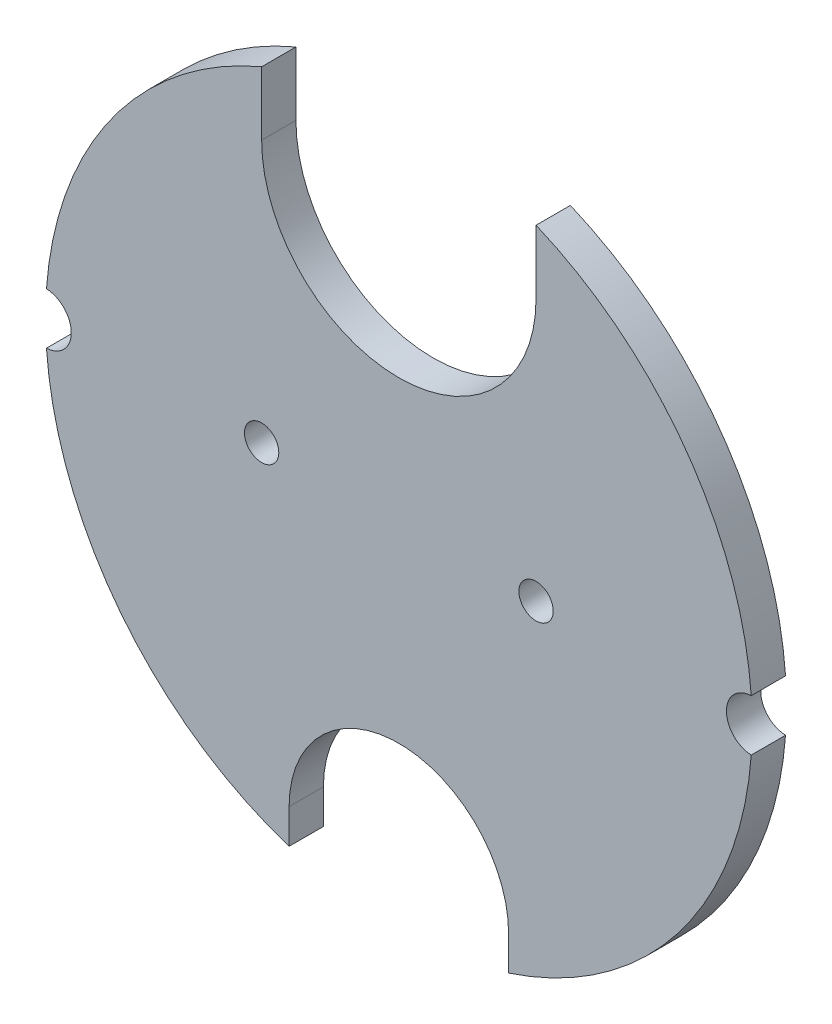
SolidWorks part; units mm, degrees
material "PC High Viscosity"
ref_plane "Front Plane" through (0, 0, 0) normal (0, 0, 1) x (1, 0, 0)
ref_plane "Top Plane" through (0, 0, 0) normal (0, 1, 0) x (1, 0, 0)
ref_plane "Right Plane" through (0, 0, 0) normal (1, 0, 0) x (0, 0, -1)
sketch "Sketch1" plane through (0, 0, 0) normal (0, 0, 1) x (1, 0, 0)
  circle A0 centre (0, 0) radius 65.405
  dimension "D1" = 130.81
extrude "Extrude1" add sketch "Sketch1" along normal blind 6.35
sketch "Sketch2" plane through (0, 0, 6.35) normal (0, 0, 1) x (1, 0, 0)
  line L0 (0, 65.405) -> (0, 48.5098) construction
  line L1 (-25.4, 48.5098) -> (-25.4, 60.2715)
  line L2 (-25.4, 60.2715) -> (-25.4, 90.805)
  line L3 (-25.4, 90.805) -> (25.4, 90.805)
  line L4 (25.4, 90.805) -> (25.4, 60.2715)
  line L5 (25.4, 60.2715) -> (25.4, 48.5098)
  line L6 (0, 0) -> (25.4, 0) construction
  line L7 (0, 0) -> (-25.4, 0) construction
  line L8 (20.32, -55.8022) -> (20.32, -68.5022)
  line L9 (20.32, -68.5022) -> (-20.32, -68.5022)
  line L10 (-20.32, -68.5022) -> (-20.32, -55.8022)
  line L11 (0, -65.405) -> (0, -76.9287) construction
  circle A0 centre (0, 0) radius 65.405 construction
  arc A1 (25.4, 48.5098) -> (-25.4, 48.5098) centre (0, 48.5098) cw
  circle A2 centre (-65.405, 0) radius 4.7625
  circle A3 centre (65.405, 0) radius 4.7625
  circle A4 centre (25.4, 0) radius 3.175
  circle A5 centre (-25.4, 0) radius 3.175
  arc A6 (-20.32, -55.8022) -> (20.32, -55.8022) centre (0, -55.8022) cw
  dimension "D1" = 25.4
  dimension "D2" = 9.525
  dimension "D3" = 6.35
  dimension "D5" = 20.32
  dimension "D4" = 25.4
  dimension "D7" = 16.8952
  dimension "D8" = 25.4
  dimension "D9" = 12.7
extrude "Extrude2" cut sketch "Sketch2" against normal through all
